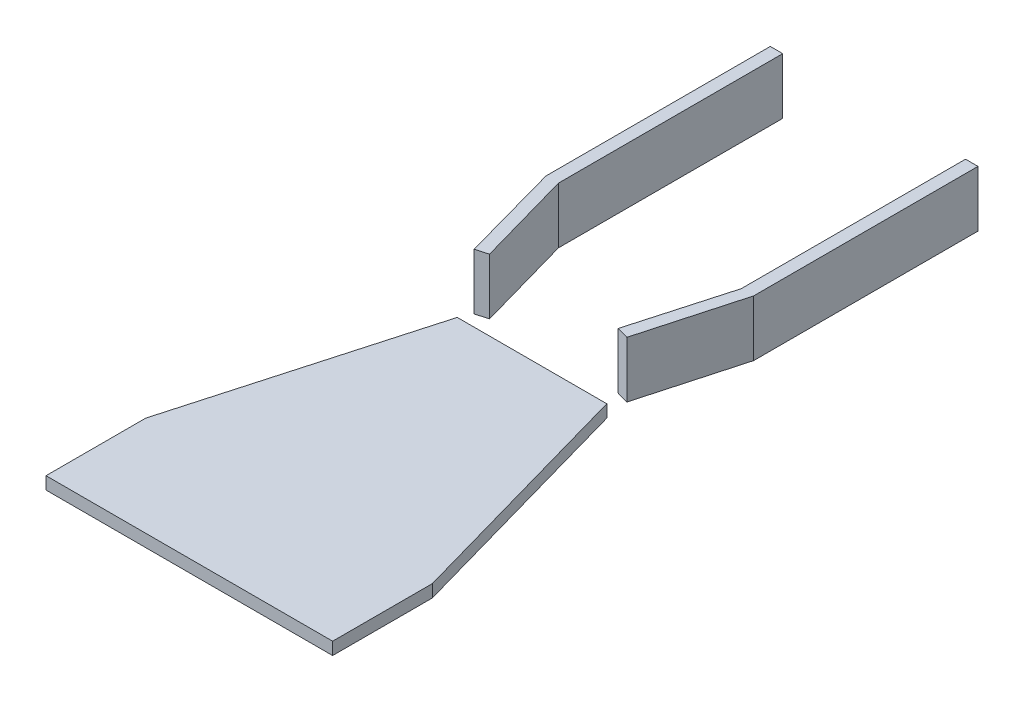
SolidWorks part; units mm, degrees
ref_plane "Front Plane" through (0, 0, 0) normal (0, 0, 1) x (1, 0, 0)
ref_plane "Top Plane" through (0, 0, 0) normal (0, 1, 0) x (1, 0, 0)
ref_plane "Right Plane" through (0, 0, 0) normal (1, 0, 0) x (0, 0, -1)
sketch "Sketch1" plane through (0, 0, 0) normal (0, 1, 0) x (1, 0, 0)
  line L6 (-44.0774, -6.8141) -> (-38.5774, 12.6859)
  line L7 (-44.0774, -14.8141) -> (-21.0774, -14.8141)
  line L8 (-44.0774, -14.8141) -> (-44.0774, -6.8141)
  line L9 (-44.0774, -6.8141) -> (-21.0774, -6.8141)
  line L10 (-21.0774, -14.8141) -> (-21.0774, -6.8141)
  line L11 (-38.5774, 12.6859) -> (-26.5774, 12.6859)
  line L12 (-26.5774, 12.6859) -> (-21.0774, -6.8141)
  line L13 (-32.5774, -14.8141) -> (-32.5774, 40.1859) construction
  line L15 (-44.0774, -6.8141) -> (-21.0774, -6.8141)
  point P0 (0, 0)
  point P15 (-32.5774, 12.6859)
  dimension "D7" = 23
  dimension "D8" = 8
  dimension "D9" = 27.5
  dimension "D10" = 12
extrude "Boss-Extrude1" add sketch "Sketch1" along normal blind 1 contours L9 L13 L11 L6 | L13 L15 L12 L11 | L13 L7 L10 L15 | L7 L13 L9 L8
sketch "Sketch3" plane through (0, 0, 0) normal (0, 1, 0) x (1, 0, 0)
  line L0 (-40.3484, 22.5758) -> (-38.1767, 14.8762)
  line L1 (-41.3484, 40.5758) -> (-40.3484, 40.5758)
  line L2 (-41.3484, 40.5758) -> (-41.3484, 22.5758)
  line L3 (-41.3484, 22.5758) -> (-40.3484, 22.5758)
  line L4 (-40.3484, 40.5758) -> (-40.3484, 22.5758)
  line L5 (-38.1767, 14.8762) -> (-39.1391, 14.6048)
  line L6 (-39.1391, 14.6048) -> (-41.3484, 22.5758)
  line L7 (-26.5774, 12.6859) -> (-21.0774, -6.8141) construction
  line L8 (-21.0774, -14.8141) -> (-21.0774, -6.8141) construction
  arc A0 (-22.6374, -1.2831) -> (-21.0774, -12.5608) centre (-21.0774, -6.8141) ccw
  point P4 (-38.6579, 14.7405)
  point P17 (0, 0)
  point P18 (0, 0)
  point P19 (0, 0)
  point P20 (0, 0)
  point P21 (0, 0)
  point P22 (0, 0)
  point P23 (0, 0)
  point P24 (0, 0)
  dimension "D1" = 1
  dimension "D2" = 1
  dimension "D3" = 8
  dimension "D4" = 18
  dimension "D5" = 164.249
extrude "Boss-Extrude2" add sketch "Sketch3" along normal blind 4.5 separate body contours L4 L1 L2 L3 | L6 L5 L0 L3
mirror "Mirror1" about plane through (-40.3484, 4.5, 0) normal (1, 0, 0) of bodies 102
move or copy body "Body-Move/Copy1" bodies to move or copy 103 copy no translate (14.668, 0, 0) parameters "D1"=14.668, "D2"=0, "D3"=0
